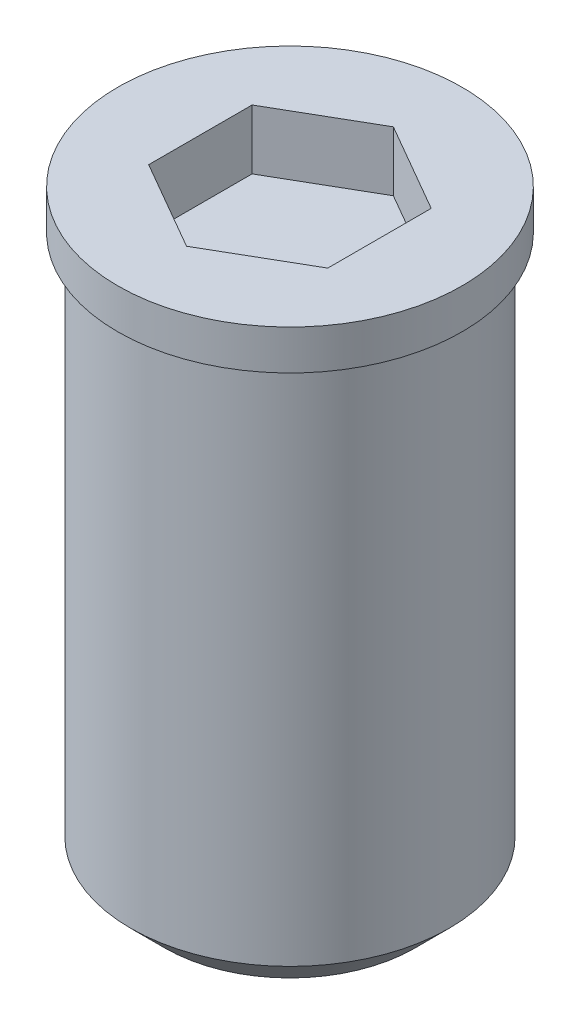
SolidWorks part; units mm, degrees
ref_plane "Спереди" through (0, 0, 0) normal (0, 0, 1) x (1, 0, 0)
ref_plane "Сверху" through (0, 0, 0) normal (0, 1, 0) x (1, 0, 0)
ref_plane "Сбоку" through (0, 0, 0) normal (1, 0, 0) x (0, 0, -1)
ref_plane "Плоскость1" through (0, 0, 0) normal (0, 0, 1) x (1, 0, 0)
sketch "Эскиз1" plane through (0, 0, 0) normal (0, 0, 1) x (1, 0, 0)
  line L0 (0, 0.5) -> (2.1622, 0.5)
  line L1 (2.1622, 0.5) -> (2.1622, 0)
  line L2 (2.1622, 0) -> (2, 0)
  line L3 (2, 0) -> (2, -6.5705)
  line L4 (2, -6.5705) -> (1.5705, -7)
  line L5 (1.5705, -7) -> (0, -7)
  line L6 (0, -7) -> (0, 0.5)
  line L7 (0, -7) -> (0, 0.5) construction
revolve "Повернуть1" add sketch "Эскиз1" angle 360 about L7
ref_plane "Плоскость2" through (0, 0.5, 0) normal (0, 1, 0) x (1, 0, 0)
sketch "Эскиз2" plane through (0, 0.5, 0) normal (0, 1, 0) x (1, 0, 0)
  line L0 (-1.125, 0.6495) -> (-1.125, -0.6495)
  line L1 (-1.125, -0.6495) -> (0, -1.299)
  line L2 (0, -1.299) -> (1.125, -0.6495)
  line L3 (1.125, -0.6495) -> (1.125, 0.6495)
  line L4 (1.125, 0.6495) -> (0, 1.299)
  line L5 (0, 1.299) -> (-1.125, 0.6495)
extrude "Вырез-Вытянуть1" cut sketch "Эскиз2" against normal blind 0.75
